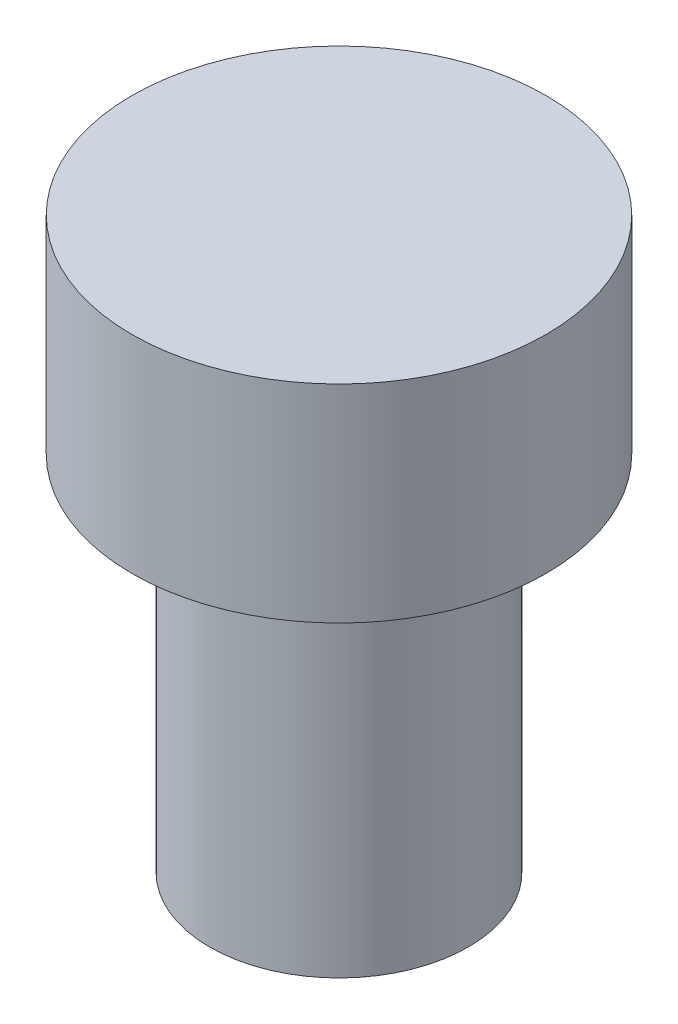
SolidWorks part; units mm, degrees
ref_plane "Front Plane" through (0, 0, 0) normal (0, 0, 1) x (1, 0, 0)
ref_plane "Top Plane" through (0, 0, 0) normal (0, 1, 0) x (1, 0, 0)
ref_plane "Right Plane" through (0, 0, 0) normal (1, 0, 0) x (0, 0, -1)
sketch "Sketch1" plane through (0, 0, 0) normal (0, 1, 0) x (1, 0, 0)
  circle A0 centre (0, 0) radius 2.5
  dimension "D1" = 5
extrude "Boss-Extrude1" add sketch "Sketch1" along normal blind 7
sketch "Sketch2" plane through (0, 7, 0) normal (0, 1, 0) x (1, 0, 0)
  circle A0 centre (0, 0) radius 4
  dimension "D1" = 8
extrude "Boss-Extrude2" add sketch "Sketch2" along normal blind 4
